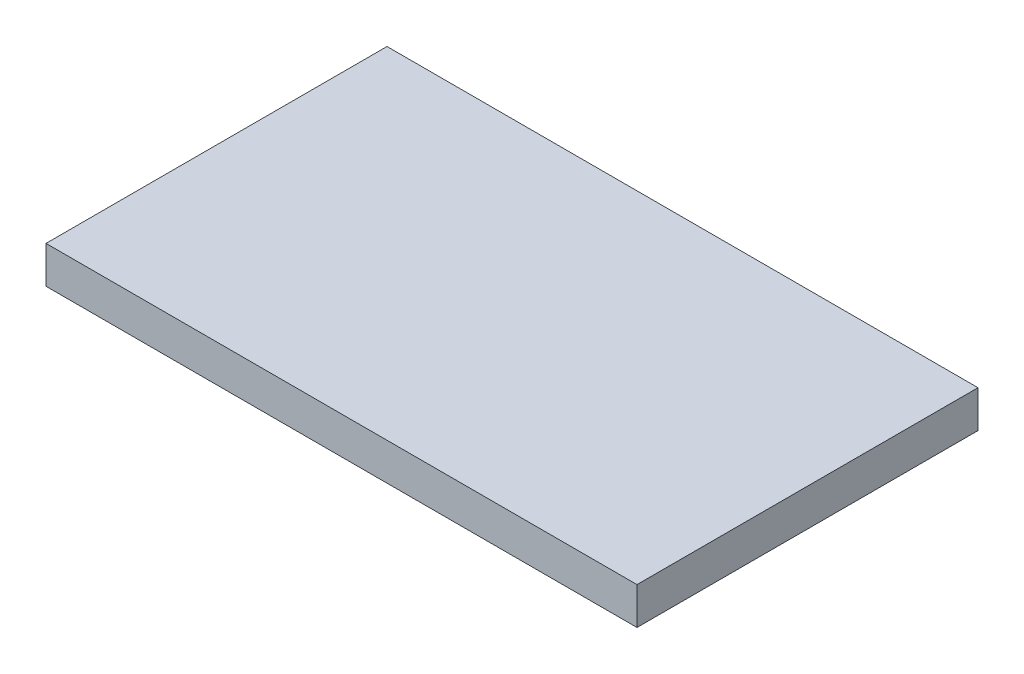
SolidWorks part; units mm, degrees
ref_plane "Front Plane" through (0, 0, 0) normal (0, 0, 1) x (1, 0, 0)
ref_plane "Top Plane" through (0, 0, 0) normal (0, 1, 0) x (1, 0, 0)
ref_plane "Right Plane" through (0, 0, 0) normal (1, 0, 0) x (0, 0, -1)
other "Configuration Table"
sketch "Sketch1" plane through (0, 0, 0) normal (0, 1, 0) x (1, 0, 0)
  line L1 (-64.6221, -37.2885) -> (64.6221, -37.2885)
  line L2 (-64.6221, -37.2885) -> (-64.6221, 37.2885)
  line L3 (-64.6221, 37.2885) -> (64.6221, 37.2885)
  line L4 (64.6221, -37.2885) -> (64.6221, 37.2885)
  line L5 (-64.6221, -37.2885) -> (64.6221, 37.2885) construction
  line L6 (-64.6221, 37.2885) -> (64.6221, -37.2885) construction
  point P0 (0, 0)
extrude "Boss-Extrude1" add sketch "Sketch1" along normal blind 8.128
